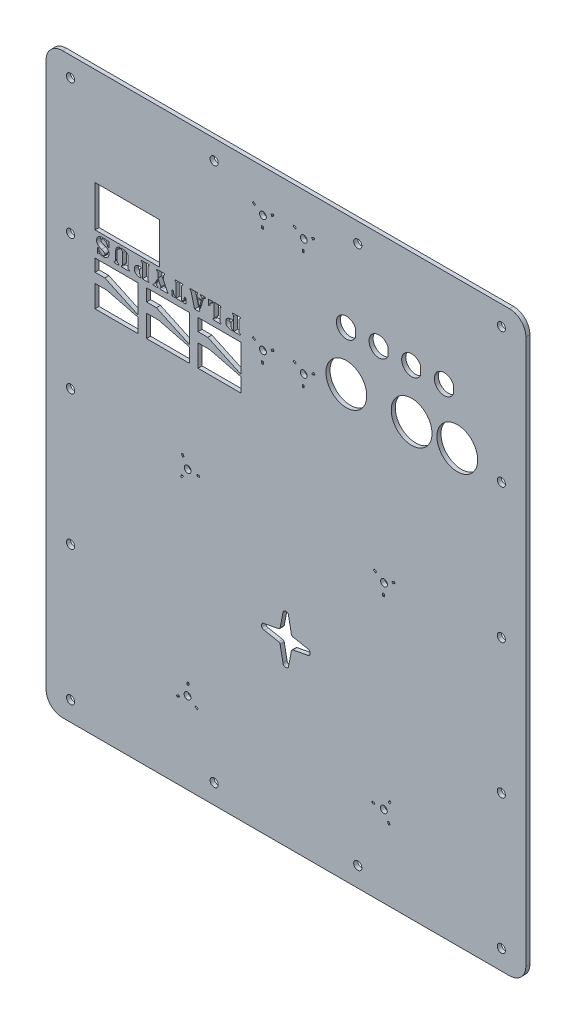
SolidWorks part; units mm, degrees
material "Acrylic (Medium-high impact)"
ref_plane "Front Plane" through (0, 0, 0) normal (0, 0, 1) x (1, 0, 0)
ref_plane "Top Plane" through (0, 0, 0) normal (0, 1, 0) x (1, 0, 0)
ref_plane "Right Plane" through (0, 0, 0) normal (1, 0, 0) x (0, 0, -1)
sketch "Sketch1" plane through (0, 0, 0) normal (0, 0, 1) x (1, 0, 0)
  line L4 (174.1369, 46.3068) -> (-173.8431, 46.3068)
  line L5 (-186.5431, 33.6068) -> (-186.5431, -390.5732)
  line L6 (-173.8431, -403.2732) -> (174.1369, -403.2732)
  line L7 (186.8369, -390.5732) -> (186.8369, 33.6068)
  line L8 (174.1369, 46.3068) -> (-173.8431, 46.3068)
  line L9 (-186.5431, 33.6068) -> (-186.5431, -390.5732)
  line L10 (-173.8431, -403.2732) -> (174.1369, -403.2732)
  line L11 (186.8369, -390.5732) -> (186.8369, 33.6068)
  arc A4 (-173.8431, 46.3068) -> (-186.5431, 33.6068) centre (-173.8431, 33.6068) ccw
  arc A5 (-186.5431, -390.5732) -> (-173.8431, -403.2732) centre (-173.8431, -390.5732) ccw
  arc A6 (174.1369, -403.2732) -> (186.8369, -390.5732) centre (174.1369, -390.5732) ccw
  arc A7 (186.8369, 33.6068) -> (174.1369, 46.3068) centre (174.1369, 33.6068) ccw
  arc A8 (-173.8431, 46.3068) -> (-186.5431, 33.6068) centre (-173.8431, 33.6068) ccw
  arc A9 (-186.5431, -390.5732) -> (-173.8431, -403.2732) centre (-173.8431, -390.5732) ccw
  arc A10 (174.1369, -403.2732) -> (186.8369, -390.5732) centre (174.1369, -390.5732) ccw
  arc A11 (186.8369, 33.6068) -> (174.1369, 46.3068) centre (174.1369, 33.6068) ccw
  dimension "D1" = 0
extrude "Boss-Extrude1" add sketch "Sketch1" along normal blind 3.175
sketch "Sketch4" plane through (0, 0, 0) normal (0, 0, -1) x (-1, 0, 0)
  circle A0 centre (167.4931, 31.0668) radius 3.175 construction
  circle A1 centre (167.4931, -73.7082) radius 3.175 construction
  circle A2 centre (167.4931, -178.4832) radius 3.175 construction
  circle A3 centre (167.4931, -283.2582) radius 3.175 construction
  circle A4 centre (167.4931, -388.0332) radius 3.175 construction
  circle A5 centre (55.7331, -388.0332) radius 3.175 construction
  circle A6 centre (-56.0269, -388.0332) radius 3.175 construction
  circle A7 centre (-167.7869, -388.0332) radius 3.175 construction
  circle A8 centre (-167.7869, -283.2582) radius 3.175 construction
  circle A9 centre (-167.7869, -178.4832) radius 3.175 construction
  circle A10 centre (-167.7869, -73.7082) radius 3.175 construction
  circle A11 centre (-167.7869, 31.0668) radius 3.175 construction
  circle A12 centre (-56.0269, 31.0668) radius 3.175 construction
  circle A13 centre (55.7331, 31.0668) radius 3.175 construction
  circle A14 centre (167.4931, 31.0668) radius 3.175
  circle A15 centre (167.4931, -73.7082) radius 3.175
  circle A16 centre (167.4931, -178.4832) radius 3.175
  circle A17 centre (167.4931, -283.2582) radius 3.175
  circle A18 centre (167.4931, -388.0332) radius 3.175
  circle A19 centre (55.7331, -388.0332) radius 3.175
  circle A20 centre (-56.0269, -388.0332) radius 3.175
  circle A21 centre (-167.7869, -388.0332) radius 3.175
  circle A22 centre (-167.7869, -283.2582) radius 3.175
  circle A23 centre (-167.7869, -178.4832) radius 3.175
  circle A24 centre (-167.7869, -73.7082) radius 3.175
  circle A25 centre (-167.7869, 31.0668) radius 3.175
  circle A26 centre (-56.0269, 31.0668) radius 3.175
  circle A27 centre (55.7331, 31.0668) radius 3.175
extrude "Cut-Extrude3" cut sketch "Sketch4" against normal through all
sketch "Sketch5" plane through (0, 0, 3.175) normal (0, 0, 1) x (1, 0, 0)
  line L1 (174.1369, 46.3068) -> (-173.8431, 46.3068) construction
  line L2 (-186.5431, 33.6068) -> (-186.5431, -390.5732) construction
  line L3 (-98.4559, -29.8932) -> (-148.4431, -29.8932)
  line L4 (-98.4559, -29.8932) -> (-98.4559, -61.8718)
  line L5 (-98.4559, -61.8718) -> (-148.4431, -61.8718)
  line L6 (-148.4431, -29.8932) -> (-148.4431, -61.8718)
  line L7 (-98.4559, -29.8932) -> (-148.4431, -61.8718) construction
  line L8 (-98.4559, -61.8718) -> (-148.4431, -29.8932) construction
  point P5 (-123.4495, -45.8825)
  dimension "D1" = 31.9786
  dimension "D2" = 49.9872
  dimension "D3" = 76.2
  dimension "D4" = 38.1
extrude "Cut-Extrude4" cut sketch "Sketch5" against normal through all
sketch "Sketch6"
  dimension "D1" = 7.62
  dimension "D2" = 7.62
  dimension "D3" = 19.05
  dimension "D4" = 25.4
extrude "Cut-Extrude5" [suppressed] cut sketch "Sketch6" against normal through all
extrude "Cut-Extrude8" cut sketch "Sketch10" against normal through all
sketch "Sketch10" plane through (13.7069, -177.2864, 3.175) normal (0, 0, 1) x (1, 0, 0)
  line L8 (-38.9984, 195.8192) -> (-39.3921, 195.1373) construction
  line L9 (-39.3921, 195.1373) -> (-38.0303, 194.351) construction
  line L10 (-38.0303, 194.351) -> (-37.6366, 195.0329) construction
  line L11 (-37.6366, 195.0329) -> (-38.9984, 195.8192) construction
  line L20 (-7.2484, 195.8192) -> (-7.6421, 195.1373) construction
  line L21 (-7.6421, 195.1373) -> (-6.2803, 194.351) construction
  line L22 (-6.2803, 194.351) -> (-5.8866, 195.0329) construction
  line L23 (-5.8866, 195.0329) -> (-7.2484, 195.8192) construction
  line L24 (8.5619, 194.4554) -> (8.1682, 195.1373) construction
  line L25 (8.1682, 195.1373) -> (6.8064, 194.351) construction
  line L26 (6.8064, 194.351) -> (7.2001, 193.6691) construction
  line L27 (7.2001, 193.6691) -> (8.5619, 194.4554) construction
  line L28 (-32.2743, 90.3861) -> (-31.4869, 90.3861) construction
  line L29 (-31.4869, 90.3861) -> (-31.4869, 91.9587) construction
  line L30 (-31.4869, 91.9587) -> (-32.2743, 91.9587) construction
  line L31 (-32.2743, 91.9587) -> (-32.2743, 90.3861) construction
  line L40 (-23.1881, 194.4554) -> (-23.5818, 195.1373) construction
  line L41 (-23.5818, 195.1373) -> (-24.9436, 194.351) construction
  line L42 (-24.9436, 194.351) -> (-24.5499, 193.6691) construction
  line L43 (-24.5499, 193.6691) -> (-23.1881, 194.4554) construction
  line L44 (-32.2743, 181.4451) -> (-31.4869, 181.4451) construction
  line L45 (-31.4869, 181.4451) -> (-31.4869, 183.0177) construction
  line L46 (-31.4869, 183.0177) -> (-32.2743, 183.0177) construction
  line L47 (-32.2743, 183.0177) -> (-32.2743, 181.4451) construction
  line L60 (-0.5243, 181.4451) -> (0.2631, 181.4451) construction
  line L61 (0.2631, 181.4451) -> (0.2631, 183.0177) construction
  line L62 (0.2631, 183.0177) -> (-0.5243, 183.0177) construction
  line L63 (-0.5243, 183.0177) -> (-0.5243, 181.4451) construction
  line L64 (-38.9984, 104.7602) -> (-39.3921, 104.0783) construction
  line L65 (-39.3921, 104.0783) -> (-38.0303, 103.292) construction
  line L66 (-38.0303, 103.292) -> (-37.6366, 103.9739) construction
  line L67 (-37.6366, 103.9739) -> (-38.9984, 104.7602) construction
  line L68 (-23.1881, 103.3964) -> (-23.5818, 104.0783) construction
  line L69 (-23.5818, 104.0783) -> (-24.9436, 103.292) construction
  line L70 (-24.9436, 103.292) -> (-24.5499, 102.6101) construction
  line L71 (-24.5499, 102.6101) -> (-23.1881, 103.3964) construction
  line L84 (-7.2484, 104.7602) -> (-7.6421, 104.0783) construction
  line L85 (-7.6421, 104.0783) -> (-6.2803, 103.292) construction
  line L86 (-6.2803, 103.292) -> (-5.8866, 103.9739) construction
  line L87 (-5.8866, 103.9739) -> (-7.2484, 104.7602) construction
  line L88 (8.5619, 103.3964) -> (8.1682, 104.0783) construction
  line L89 (8.1682, 104.0783) -> (6.8064, 103.292) construction
  line L90 (6.8064, 103.292) -> (7.2001, 102.6101) construction
  line L91 (7.2001, 102.6101) -> (8.5619, 103.3964) construction
  line L92 (-0.5243, 90.3861) -> (0.2631, 90.3861) construction
  line L93 (0.2631, 90.3861) -> (0.2631, 91.9587) construction
  line L94 (0.2631, 91.9587) -> (-0.5243, 91.9587) construction
  line L95 (-0.5243, 91.9587) -> (-0.5243, 90.3861) construction
  line L108 (-39.0914, 196.1662) -> (-39.7391, 195.0443)
  line L109 (-39.7391, 195.0443) -> (-37.9373, 194.0041)
  line L110 (-37.9373, 194.0041) -> (-37.2896, 195.1259)
  line L111 (-37.2896, 195.1259) -> (-39.0914, 196.1662)
  line L112 (-22.8411, 194.3624) -> (-23.4888, 195.4843)
  line L113 (-23.4888, 195.4843) -> (-25.2906, 194.444)
  line L114 (-25.2906, 194.444) -> (-24.6429, 193.3221)
  line L115 (-24.6429, 193.3221) -> (-22.8411, 194.3624)
  line L116 (-32.5283, 181.1911) -> (-31.2329, 181.1911)
  line L117 (-31.2329, 181.1911) -> (-31.2329, 183.2717)
  line L118 (-31.2329, 183.2717) -> (-32.5283, 183.2717)
  line L119 (-32.5283, 183.2717) -> (-32.5283, 181.1911)
  line L120 (-7.3414, 196.1662) -> (-7.9891, 195.0443)
  line L121 (-7.9891, 195.0443) -> (-6.1873, 194.0041)
  line L122 (-6.1873, 194.0041) -> (-5.5396, 195.1259)
  line L123 (-5.5396, 195.1259) -> (-7.3414, 196.1662)
  line L124 (8.9089, 194.3624) -> (8.2612, 195.4843)
  line L125 (8.2612, 195.4843) -> (6.4594, 194.444)
  line L126 (6.4594, 194.444) -> (7.1071, 193.3221)
  line L127 (7.1071, 193.3221) -> (8.9089, 194.3624)
  line L128 (-0.7783, 181.1911) -> (0.5171, 181.1911)
  line L129 (0.5171, 181.1911) -> (0.5171, 183.2717)
  line L130 (0.5171, 183.2717) -> (-0.7783, 183.2717)
  line L131 (-0.7783, 183.2717) -> (-0.7783, 181.1911)
  line L132 (-39.0914, 105.1072) -> (-39.7391, 103.9853)
  line L133 (-39.7391, 103.9853) -> (-37.9373, 102.9451)
  line L134 (-37.9373, 102.9451) -> (-37.2896, 104.0669)
  line L135 (-37.2896, 104.0669) -> (-39.0914, 105.1072)
  line L136 (-22.8411, 103.3034) -> (-23.4888, 104.4253)
  line L137 (-23.4888, 104.4253) -> (-25.2906, 103.385)
  line L138 (-25.2906, 103.385) -> (-24.6429, 102.2631)
  line L139 (-24.6429, 102.2631) -> (-22.8411, 103.3034)
  line L140 (-32.5283, 90.1321) -> (-31.2329, 90.1321)
  line L141 (-31.2329, 90.1321) -> (-31.2329, 92.2127)
  line L142 (-31.2329, 92.2127) -> (-32.5283, 92.2127)
  line L143 (-32.5283, 92.2127) -> (-32.5283, 90.1321)
  line L144 (-7.3414, 105.1072) -> (-7.9891, 103.9853)
  line L145 (-7.9891, 103.9853) -> (-6.1873, 102.9451)
  line L146 (-6.1873, 102.9451) -> (-5.5396, 104.0669)
  line L147 (-5.5396, 104.0669) -> (-7.3414, 105.1072)
  line L148 (8.9089, 103.3034) -> (8.2612, 104.4253)
  line L149 (8.2612, 104.4253) -> (6.4594, 103.385)
  line L150 (6.4594, 103.385) -> (7.1071, 102.2631)
  line L151 (7.1071, 102.2631) -> (8.9089, 103.3034)
  line L152 (-0.7783, 90.1321) -> (0.5171, 90.1321)
  line L153 (0.5171, 90.1321) -> (0.5171, 92.2127)
  line L154 (0.5171, 92.2127) -> (-0.7783, 92.2127)
  line L155 (-0.7783, 92.2127) -> (-0.7783, 90.1321)
  circle A4 centre (-31.4869, 190.5732) radius 2.6543
  circle A5 centre (0.2631, 190.5732) radius 2.6543
  circle A6 centre (-31.4869, 99.5142) radius 2.6543
  circle A7 centre (0.2631, 99.5142) radius 2.6543
extrude "Cut-Extrude9" cut sketch "Sketch11" against normal through all
sketch "Sketch11" plane through (13.7069, -177.2864, 3.175) normal (0, 0, 1) x (1, 0, 0)
  line L0 (-13.7069, -86.2868) -> (94.347, -86.2868) construction
  line L1 (-13.7069, -86.2868) -> (90.6919, -58.4207) construction
  line L16 (-11.4844, -103.0635) -> (-9.33, -91.8721)
  line L17 (-8.1216, -90.6637) -> (3.0698, -88.5093)
  line L18 (3.0698, -84.0643) -> (-8.1216, -81.9098)
  line L19 (-9.33, -80.7014) -> (-11.4844, -69.5101)
  line L20 (-15.9294, -69.5101) -> (-18.0839, -80.7014)
  line L21 (-19.2923, -81.9098) -> (-30.4836, -84.0643)
  line L22 (-30.4836, -88.5093) -> (-19.2923, -90.6637)
  line L23 (-18.0839, -91.8721) -> (-15.9294, -103.0635)
  line L50 (-93.8283, -1.1619) -> (-94.9502, -1.8096)
  line L51 (-94.9502, -1.8096) -> (-93.9099, -3.6114)
  line L52 (-93.9099, -3.6114) -> (-92.788, -2.9637)
  line L53 (-92.788, -2.9637) -> (-93.8283, -1.1619)
  line L54 (-80.657, -10.8491) -> (-80.657, -9.5537)
  line L55 (-80.657, -9.5537) -> (-82.7375, -9.5537)
  line L56 (-82.7375, -9.5537) -> (-82.7375, -10.8491)
  line L57 (-82.7375, -10.8491) -> (-80.657, -10.8491)
  line L58 (-95.6321, -17.4122) -> (-94.5102, -18.0599)
  line L59 (-94.5102, -18.0599) -> (-93.4699, -16.2581)
  line L60 (-93.4699, -16.2581) -> (-94.5918, -15.6104)
  line L61 (-94.5918, -15.6104) -> (-95.6321, -17.4122)
  line L62 (55.1676, -4.3616) -> (54.5199, -5.4835)
  line L63 (54.5199, -5.4835) -> (56.3217, -6.5238)
  line L64 (56.3217, -6.5238) -> (56.9694, -5.4019)
  line L65 (56.9694, -5.4019) -> (55.1676, -4.3616)
  line L66 (71.418, -6.1654) -> (70.7703, -5.0436)
  line L67 (70.7703, -5.0436) -> (68.9684, -6.0838)
  line L68 (68.9684, -6.0838) -> (69.6161, -7.2057)
  line L69 (69.6161, -7.2057) -> (71.418, -6.1654)
  line L70 (61.7307, -19.3367) -> (63.0261, -19.3367)
  line L71 (63.0261, -19.3367) -> (63.0261, -17.2562)
  line L72 (63.0261, -17.2562) -> (61.7307, -17.2562)
  line L73 (61.7307, -17.2562) -> (61.7307, -19.3367)
  line L74 (-98.8318, -166.4081) -> (-98.1841, -167.53)
  line L75 (-98.1841, -167.53) -> (-96.3823, -166.4897)
  line L76 (-96.3823, -166.4897) -> (-97.03, -165.3679)
  line L77 (-97.03, -165.3679) -> (-98.8318, -166.4081)
  line L78 (-82.5815, -168.2119) -> (-81.9338, -167.09)
  line L79 (-81.9338, -167.09) -> (-83.7356, -166.0498)
  line L80 (-83.7356, -166.0498) -> (-84.3833, -167.1716)
  line L81 (-84.3833, -167.1716) -> (-82.5815, -168.2119)
  line L82 (-89.1446, -153.2368) -> (-90.44, -153.2368)
  line L83 (-90.44, -153.2368) -> (-90.44, -155.3174)
  line L84 (-90.44, -155.3174) -> (-89.1446, -155.3174)
  line L85 (-89.1446, -155.3174) -> (-89.1446, -153.2368)
  line L86 (53.2431, -161.7244) -> (53.2431, -163.0198)
  line L87 (53.2431, -163.0198) -> (55.3237, -163.0198)
  line L88 (55.3237, -163.0198) -> (55.3237, -161.7244)
  line L89 (55.3237, -161.7244) -> (53.2431, -161.7244)
  line L90 (68.2182, -155.1613) -> (67.0963, -154.5136)
  line L91 (67.0963, -154.5136) -> (66.056, -156.3155)
  line L92 (66.056, -156.3155) -> (67.1779, -156.9632)
  line L93 (67.1779, -156.9632) -> (68.2182, -155.1613)
  line L94 (66.4144, -171.4117) -> (67.5363, -170.764)
  line L95 (67.5363, -170.764) -> (66.496, -168.9622)
  line L96 (66.496, -168.9622) -> (65.3741, -169.6099)
  line L97 (65.3741, -169.6099) -> (66.4144, -171.4117)
  line L158 (-80.911, -10.5951) -> (-80.911, -9.8077) construction
  line L159 (-80.911, -9.8077) -> (-82.4835, -9.8077) construction
  line L160 (-82.4835, -9.8077) -> (-82.4835, -10.5951) construction
  line L161 (-82.4835, -10.5951) -> (-80.911, -10.5951) construction
  line L162 (-93.9213, -1.5088) -> (-94.6032, -1.9025) construction
  line L163 (-94.6032, -1.9025) -> (-93.8169, -3.2644) construction
  line L164 (-93.8169, -3.2644) -> (-93.135, -2.8707) construction
  line L165 (-93.135, -2.8707) -> (-93.9213, -1.5088) construction
  line L166 (-95.2851, -17.3192) -> (-94.6032, -17.7129) construction
  line L167 (-94.6032, -17.7129) -> (-93.8169, -16.351) construction
  line L168 (-93.8169, -16.351) -> (-94.4988, -15.9573) construction
  line L169 (-94.4988, -15.9573) -> (-95.2851, -17.3192) construction
  line L182 (55.2606, -4.7086) -> (54.8669, -5.3905) construction
  line L183 (54.8669, -5.3905) -> (56.2288, -6.1768) construction
  line L184 (56.2288, -6.1768) -> (56.6225, -5.4949) construction
  line L185 (56.6225, -5.4949) -> (55.2606, -4.7086) construction
  line L186 (71.071, -6.0724) -> (70.6773, -5.3905) construction
  line L187 (70.6773, -5.3905) -> (69.3154, -6.1768) construction
  line L188 (69.3154, -6.1768) -> (69.7091, -6.8587) construction
  line L189 (69.7091, -6.8587) -> (71.071, -6.0724) construction
  line L190 (61.9847, -19.0827) -> (62.7721, -19.0827) construction
  line L191 (62.7721, -19.0827) -> (62.7721, -17.5102) construction
  line L192 (62.7721, -17.5102) -> (61.9847, -17.5102) construction
  line L193 (61.9847, -17.5102) -> (61.9847, -19.0827) construction
  line L206 (66.5074, -171.0647) -> (67.1893, -170.671) construction
  line L207 (67.1893, -170.671) -> (66.403, -169.3091) construction
  line L208 (66.403, -169.3091) -> (65.7211, -169.7028) construction
  line L209 (65.7211, -169.7028) -> (66.5074, -171.0647) construction
  line L210 (53.4971, -161.9784) -> (53.4971, -162.7658) construction
  line L211 (53.4971, -162.7658) -> (55.0697, -162.7658) construction
  line L212 (55.0697, -162.7658) -> (55.0697, -161.9784) construction
  line L213 (55.0697, -161.9784) -> (53.4971, -161.9784) construction
  line L214 (67.8712, -155.2543) -> (67.1893, -154.8606) construction
  line L215 (67.1893, -154.8606) -> (66.403, -156.2225) construction
  line L216 (66.403, -156.2225) -> (67.0849, -156.6162) construction
  line L217 (67.0849, -156.6162) -> (67.8712, -155.2543) construction
  line L230 (-89.3986, -153.4908) -> (-90.186, -153.4908) construction
  line L231 (-90.186, -153.4908) -> (-90.186, -155.0634) construction
  line L232 (-90.186, -155.0634) -> (-89.3986, -155.0634) construction
  line L233 (-89.3986, -155.0634) -> (-89.3986, -153.4908) construction
  line L234 (-82.6745, -167.8649) -> (-82.2808, -167.183) construction
  line L235 (-82.2808, -167.183) -> (-83.6427, -166.3967) construction
  line L236 (-83.6427, -166.3967) -> (-84.0364, -167.0786) construction
  line L237 (-84.0364, -167.0786) -> (-82.6745, -167.8649) construction
  line L238 (-98.4849, -166.5011) -> (-98.0912, -167.183) construction
  line L239 (-98.0912, -167.183) -> (-96.7293, -166.3967) construction
  line L240 (-96.7293, -166.3967) -> (-97.123, -165.7148) construction
  line L241 (-97.123, -165.7148) -> (-98.4849, -166.5011) construction
  circle A0 centre (-13.7069, -86.2868) radius 108.0539 construction
  circle A1 centre (-13.7069, -86.2868) radius 114.3 construction
  circle A2 centre (90.6919, -58.4207) radius 3.81 construction
  circle A4 centre (62.6252, -162.7658) radius 3.81 construction
  circle A7 centre (-90.186, -162.6189) radius 3.81 construction
  arc A16 (-15.9294, -103.0635) -> (-11.4844, -103.0635) centre (-13.7069, -103.0635) ccw
  arc A17 (-8.1216, -90.6637) -> (-9.33, -91.8721) centre (-7.8335, -92.1602) ccw
  arc A18 (3.0698, -88.5093) -> (3.0698, -84.0643) centre (3.0698, -86.2868) ccw
  arc A19 (-9.33, -80.7014) -> (-8.1216, -81.9098) centre (-7.8335, -80.4133) ccw
  arc A20 (-11.4844, -69.5101) -> (-15.9294, -69.5101) centre (-13.7069, -69.5101) ccw
  arc A21 (-19.2923, -81.9098) -> (-18.0839, -80.7014) centre (-19.5804, -80.4133) ccw
  arc A22 (-30.4836, -84.0643) -> (-30.4836, -88.5093) centre (-30.4836, -86.2868) ccw
  arc A23 (-18.0839, -91.8721) -> (-19.2923, -90.6637) centre (-19.5804, -92.1602) ccw
  circle A26 centre (-90.0391, -9.8077) radius 3.81 construction
  circle A29 centre (62.7721, -9.9546) radius 3.81 construction
  circle A165 centre (-90.0391, -9.8077) radius 2.6543
  circle A173 centre (62.7721, -9.9546) radius 2.6543
  circle A181 centre (62.6252, -162.7658) radius 2.6543
  circle A189 centre (-90.186, -162.6189) radius 2.6543
  point P56 (-13.7069, -86.2868)
extrude "Cut-Extrude13" cut sketch "Sketch14" against normal through all
sketch "Sketch14" plane through (13.7069, -177.2864, 15.875) normal (0, 0, 1) x (1, 0, 0)
  line L7 (128.8069, 104.8938) -> (128.8069, 113.6926)
  line L8 (116.6657, 144.1508) -> (116.6657, 150.6357)
  line L9 (91.2657, 144.1508) -> (91.2657, 150.6357)
  line L10 (93.2469, 104.8938) -> (93.2469, 113.6926)
  line L11 (65.8657, 144.1508) -> (65.8657, 150.6357)
  line L12 (40.4657, 144.1508) -> (40.4657, 150.6357)
  line L13 (42.4469, 104.8938) -> (42.4469, 113.6926)
  arc A7 (128.8069, 113.6926) -> (128.8069, 104.8938) centre (119.7899, 109.2932) ccw
  arc A8 (116.6657, 150.6357) -> (116.6657, 144.1508) centre (109.6299, 147.3932) ccw
  arc A9 (91.2657, 150.6357) -> (91.2657, 144.1508) centre (84.2299, 147.3932) ccw
  arc A10 (93.2469, 113.6926) -> (93.2469, 104.8938) centre (84.2299, 109.2932) ccw
  arc A11 (65.8657, 150.6357) -> (65.8657, 144.1508) centre (58.8299, 147.3932) ccw
  arc A12 (40.4657, 150.6357) -> (40.4657, 144.1508) centre (33.4299, 147.3932) ccw
  arc A13 (42.4469, 113.6926) -> (42.4469, 104.8938) centre (33.4299, 109.2932) ccw
sketch "Sketch12" plane through (0, 0, 3.175) normal (0, 0, 1) x (1, 0, 0)
  line L0 (-34.708, -80.8136) -> (-68.2807, -80.8136)
  line L1 (-68.2807, -80.8136) -> (-68.2807, -90.4058)
  line L2 (-68.2807, -90.4058) -> (-60.6506, -90.4058)
  line L3 (-60.6506, -90.4058) -> (-34.708, -102.5051)
  line L4 (-34.708, -102.5051) -> (-34.708, -80.8136)
  line L5 (-68.2807, -97.927) -> (-59.0155, -97.927)
  line L6 (-59.0155, -97.927) -> (-34.708, -104.0311)
  line L7 (-34.708, -104.0311) -> (-34.708, -115.0404)
  line L8 (-34.708, -115.0404) -> (-68.2807, -115.0404)
  line L9 (-68.2807, -115.0404) -> (-68.2807, -97.927)
  line L10 (-74.7892, -80.8136) -> (-108.3619, -80.8136)
  line L11 (-108.3619, -80.8136) -> (-108.3619, -90.4058)
  line L12 (-108.3619, -90.4058) -> (-100.7318, -90.4058)
  line L13 (-100.7318, -90.4058) -> (-74.7892, -102.5051)
  line L14 (-74.7892, -102.5051) -> (-74.7892, -80.8136)
  line L15 (-108.3619, -97.927) -> (-99.0967, -97.927)
  line L16 (-99.0967, -97.927) -> (-74.7892, -104.0311)
  line L17 (-74.7892, -104.0311) -> (-74.7892, -115.0404)
  line L18 (-74.7892, -115.0404) -> (-108.3619, -115.0404)
  line L19 (-108.3619, -115.0404) -> (-108.3619, -97.927)
  line L20 (-114.8704, -80.8136) -> (-148.4431, -80.8136)
  line L21 (-148.4431, -80.8136) -> (-148.4431, -90.4058)
  line L22 (-148.4431, -90.4058) -> (-140.813, -90.4058)
  line L23 (-140.813, -90.4058) -> (-114.8704, -102.5051)
  line L24 (-114.8704, -102.5051) -> (-114.8704, -80.8136)
  line L25 (-148.4431, -97.927) -> (-139.1779, -97.927)
  line L26 (-139.1779, -97.927) -> (-114.8704, -104.0311)
  line L27 (-114.8704, -104.0311) -> (-114.8704, -115.0404)
  line L28 (-114.8704, -115.0404) -> (-148.4431, -115.0404)
  line L29 (-148.4431, -115.0404) -> (-148.4431, -97.927)
  line L30 (-34.708, -64.3036) -> (-148.4431, -64.3036) construction
  line L32 (-148.4431, -29.8932) -> (-148.4431, -61.8718) construction
  text T0 "Platypus" font "Stencil Std" height in points 46
  dimension "D2" = 113.7352
  dimension "D1" = 3
extrude "Cut-Extrude11" cut sketch "Sketch12" against normal through all
sketch "Sketch15" plane through (0, 0, 3.175) normal (0, 0, 1) x (1, 0, 0)
  line L0 (47.1369, 158.0449) -> (123.3369, 158.0449)
  line L1 (47.1369, 132.6449) -> (123.3369, 132.6449)
  circle A0 centre (47.1369, -67.9932) radius 15.875
  circle A1 centre (97.9369, -67.9932) radius 15.875
  circle A2 centre (133.4969, -67.9932) radius 15.875
  circle A3 centre (47.1369, 145.3449) radius 12.7
  circle A6 centre (123.3369, 145.3449) radius 12.7
  dimension "D1" = 31.75
  dimension "D2" = 25.4
extrude "Cut-Extrude14" cut sketch "Sketch15" against normal through all contours A0 | A1 | A2 | A6 L0 A3 L1 | A6 | A3
